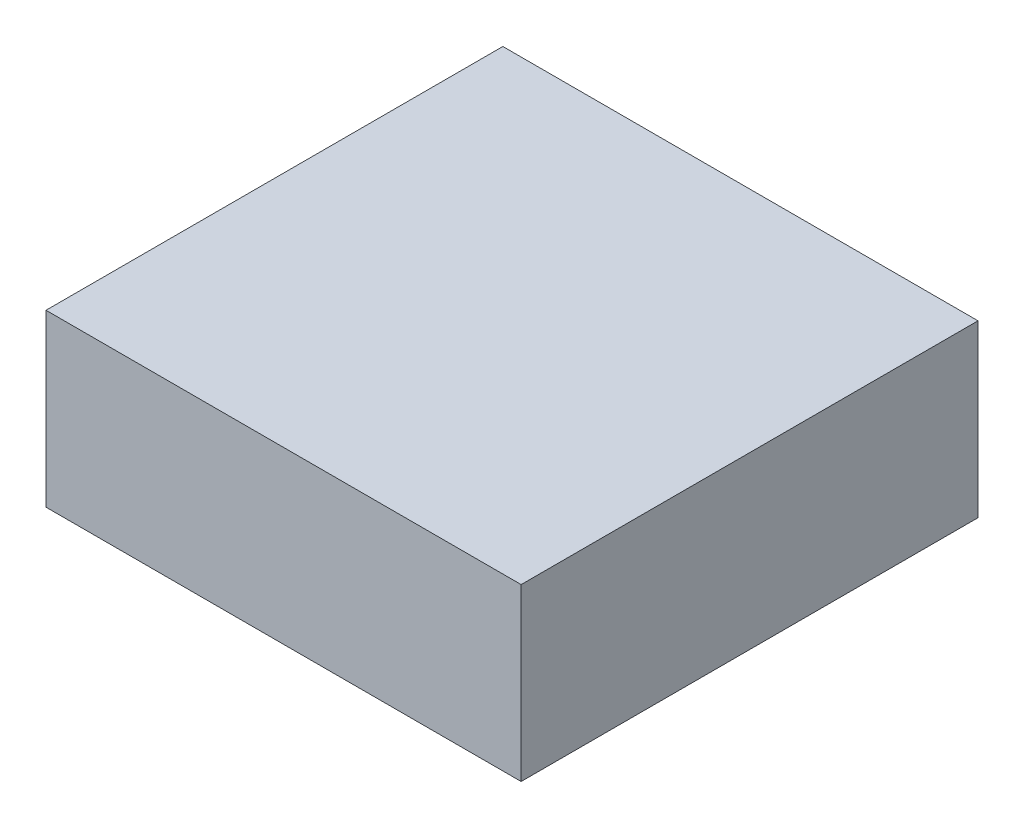
SolidWorks part; units mm, degrees
ref_plane "Front Plane" through (0, 0, 0) normal (0, 0, 1) x (1, 0, 0)
ref_plane "Top Plane" through (0, 0, 0) normal (0, 1, 0) x (1, 0, 0)
ref_plane "Right Plane" through (0, 0, 0) normal (1, 0, 0) x (0, 0, -1)
sketch "Sketch1" plane through (0, 0, 0) normal (0, 1, 0) x (1, 0, 0)
  line L1 (0, 0) -> (78, 0)
  line L2 (0, 0) -> (0, 75)
  line L3 (0, 75) -> (78, 75)
  line L4 (78, 0) -> (78, 75)
  dimension "D1" = 75
  dimension "D2" = 78
extrude "Boss-Extrude1" add sketch "Sketch1" along normal blind 28 contours L2 L1 L4 L3
sketch "Sketch2" plane through (0, 28, 0) normal (0, 1, 0) x (1, 0, 0)
  text T0 "COM100 LIGHTWEIGHT \r\nOEM AIS RECEIVER"
